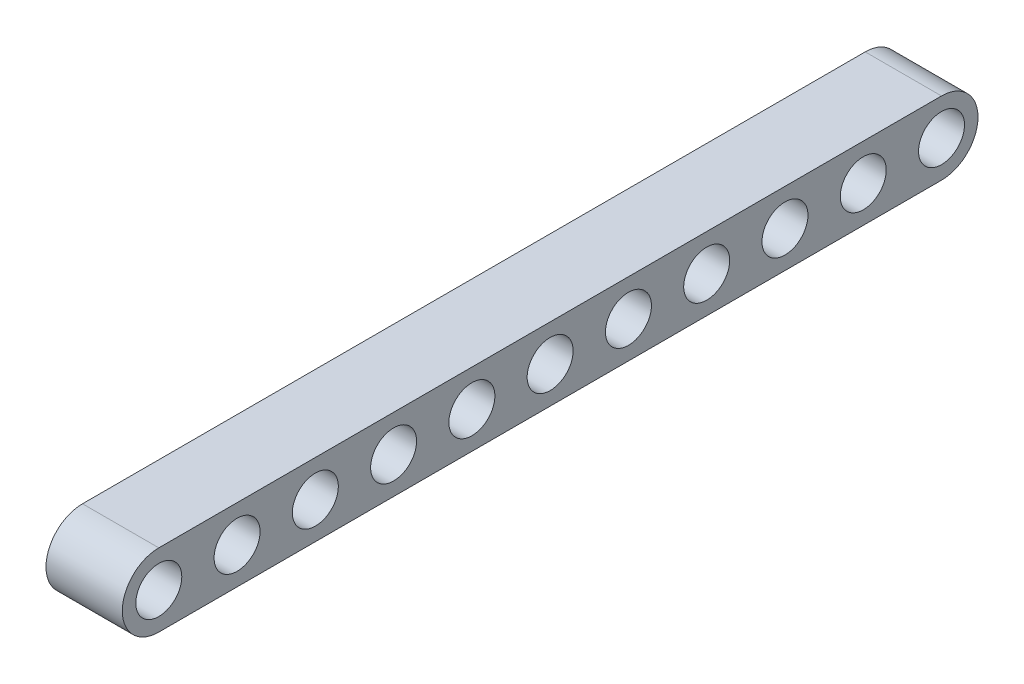
SolidWorks part; units mm, degrees
ref_plane "Front Plane" through (0, 0, 0) normal (0, 0, 1) x (1, 0, 0)
ref_plane "Top Plane" through (0, 0, 0) normal (0, 1, 0) x (1, 0, 0)
ref_plane "Right Plane" through (0, 0, 0) normal (1, 0, 0) x (0, 0, -1)
sketch "Sketch1" plane through (0, 0, 0) normal (1, 0, 0) x (0, 0, -1)
  line L0 (-40, 0) -> (40, 0) construction
  line L1 (-40, 3.73) -> (40, 3.73) construction
  line L2 (-40, 3.73) -> (-40, -3.73) construction
  line L3 (-40, -3.73) -> (40, -3.73) construction
  line L4 (40, 3.73) -> (40, -3.73) construction
  line L5 (-40, 3.73) -> (40, -3.73) construction
  line L6 (-40, -3.73) -> (40, 3.73) construction
  line L8 (-40, -3.73) -> (40, -3.73)
  line L10 (-40, 3.73) -> (40, 3.73)
  line L12 (-40, -3.73) -> (40, 3.73) construction
  line L13 (-40, 3.73) -> (40, -3.73) construction
  circle A0 centre (-40, 0) radius 2.35
  circle A1 centre (-32, 0) radius 2.35
  circle A2 centre (-24, 0) radius 2.35
  circle A3 centre (-16, 0) radius 2.35
  circle A4 centre (-8, 0) radius 2.35
  circle A5 centre (0, 0) radius 2.35
  circle A6 centre (8, 0) radius 2.35
  circle A7 centre (16, 0) radius 2.35
  circle A8 centre (24, 0) radius 2.35
  circle A9 centre (32, 0) radius 2.35
  circle A10 centre (40, 0) radius 2.35
  arc A12 (-40, 3.73) -> (-40, -3.73) centre (-40, 0) ccw
  arc A13 (40, -3.73) -> (40, 3.73) centre (40, 0) ccw
  point P0 (0, 0)
  point P9 (0, 0)
  dimension "D3" = 4.7
  dimension "D5" = 8
  dimension "D1" = 80
  dimension "D2" = 7.46
  dimension "D4" = 11
extrude "Boss-Extrude1" add sketch "Sketch1" along normal blind 7.8
